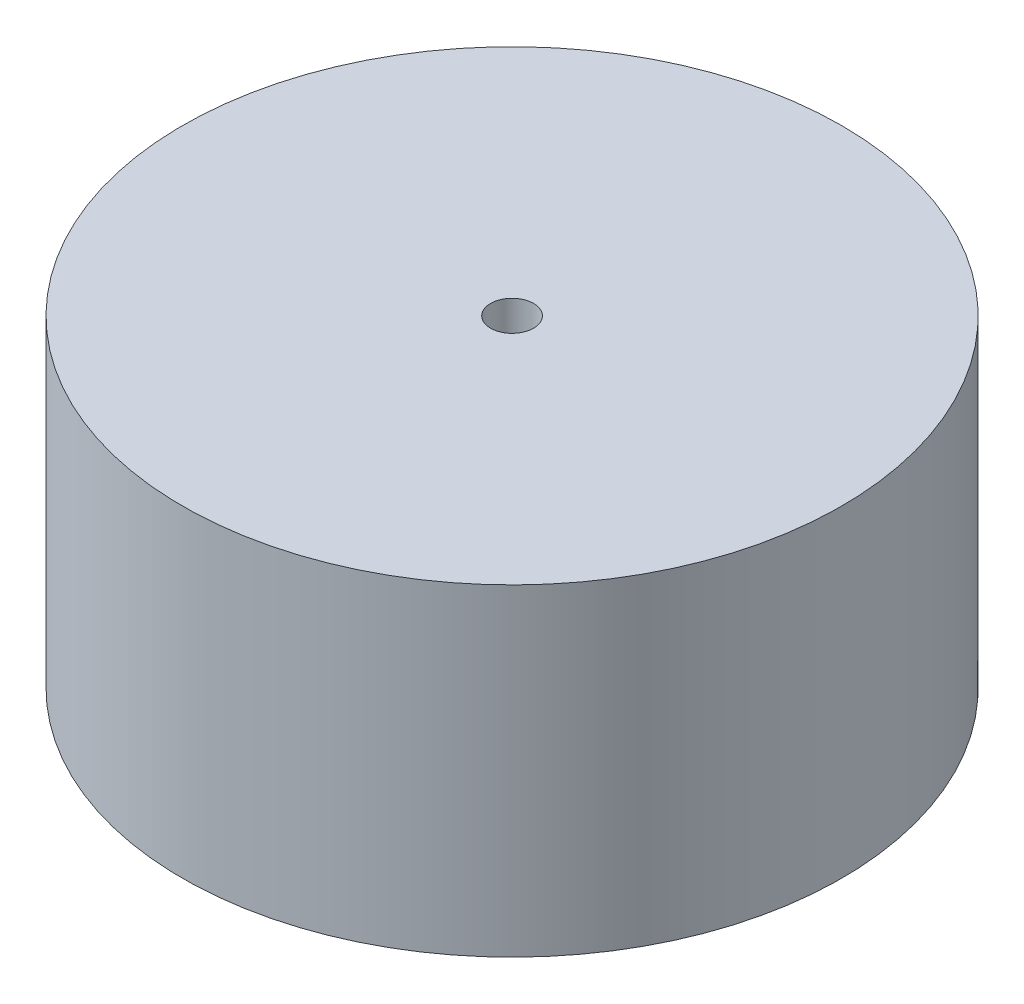
SolidWorks part; units mm, degrees
ref_plane "Front Plane" through (0, 0, 0) normal (0, 0, 1) x (1, 0, 0)
ref_plane "Top Plane" through (0, 0, 0) normal (0, 1, 0) x (1, 0, 0)
ref_plane "Right Plane" through (0, 0, 0) normal (1, 0, 0) x (0, 0, -1)
sketch "Sketch1" plane through (0, 0, 0) normal (0, 1, 0) x (1, 0, 0)
  circle A0 centre (-29.7253, 4.3466) radius 23
  dimension "D1" = 46
extrude "Boss-Extrude1" add sketch "Sketch1" along normal blind 22.5 contours A0
sketch "Sketch3" plane through (0, 0, 0) normal (0, -1, 0) x (1, 0, 0)
  circle A0 centre (-29.7253, -4.3466) radius 1.5
  dimension "D1" = 3
extrude "Cut-Extrude1" cut sketch "Sketch3" against normal through all
